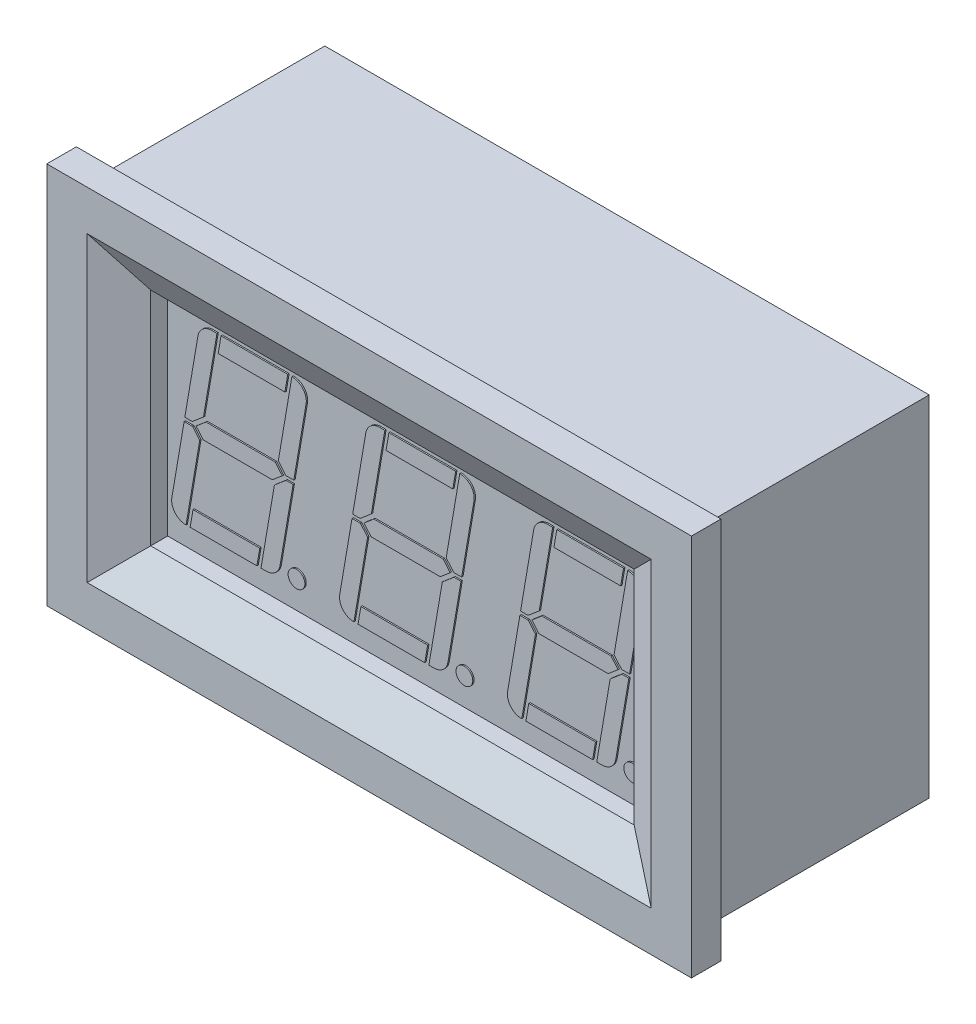
SolidWorks part; units mm, degrees
material "ABS"
ref_plane "Спереди" through (0, 0, 0) normal (0, 0, 1) x (1, 0, 0)
ref_plane "Сверху" through (0, 0, 0) normal (0, 1, 0) x (1, 0, 0)
ref_plane "Справа" through (0, 0, 0) normal (1, 0, 0) x (0, 0, -1)
sketch "Эскиз1" plane through (0, 0, 0) normal (0, 0, 1) x (1, 0, 0)
  line L1 (22.5, -13) -> (-22.5, -13)
  line L2 (22.5, -13) -> (22.5, 13)
  line L3 (22.5, 13) -> (-22.5, 13)
  line L4 (-22.5, -13) -> (-22.5, 13)
  line L5 (22.5, -13) -> (-22.5, 13) construction
  line L6 (22.5, 13) -> (-22.5, -13) construction
  point P0 (0, 0)
  dimension "D1" = 26
  dimension "D2" = 45
extrude "Бобышка-Вытянуть1" add sketch "Эскиз1" along normal blind 17
sketch "Эскиз2" plane through (0, 0, 17) normal (0, 0, 1) x (1, 0, 0)
  line L1 (24, -14.25) -> (-24, -14.25)
  line L2 (24, -14.25) -> (24, 14.25)
  line L3 (24, 14.25) -> (-24, 14.25)
  line L4 (-24, -14.25) -> (-24, 14.25)
  line L5 (24, -14.25) -> (-24, 14.25) construction
  line L6 (24, 14.25) -> (-24, -14.25) construction
  point P0 (0, 0)
  dimension "D1" = 28.5
  dimension "D2" = 48
extrude "Бобышка-Вытянуть2" add sketch "Эскиз2" along normal blind 2.2
sketch "Эскиз3" plane through (0, 0, 19.2) normal (0, 0, 1) x (1, 0, 0)
  line L1 (18, -8.25) -> (-18, -8.25)
  line L2 (18, -8.25) -> (18, 8.25)
  line L3 (18, 8.25) -> (-18, 8.25)
  line L4 (-18, -8.25) -> (-18, 8.25)
  line L5 (18, -8.25) -> (-18, 8.25) construction
  line L6 (18, 8.25) -> (-18, -8.25) construction
  point P0 (0, 0)
  dimension "D1" = 36
  dimension "D2" = 16.5
extrude "Вырез-Вытянуть1" cut sketch "Эскиз3" against normal blind 3
chamfer "Фаска1" distance 3 angle 30 4 edges at (18, 0, 19.2) (0, 8.25, 19.2) (-18, 0, 19.2) (0, -8.25, 19.2)
sketch "Эскиз4" plane through (0, 0, 16.2) normal (0, 0, 1) x (1, 0, 0)
  line L0 (-17.8, -6.75) -> (-16.532, -6.75)
  line L1 (-17.8, -6.75) -> (-16.6756, -0.15)
  line L2 (-9.6847, -6.75) -> (-8.5603, -0.15)
  line L3 (-15.5, 6.75) -> (-14.232, 6.75)
  line L4 (-18, -8.25) -> (18, -8.25) construction
  line L5 (18, 8.25) -> (-18, 8.25) construction
  line L6 (-18, 8.25) -> (-18, -8.25) construction
  line L7 (-8.5347, 0) -> (-16.65, 0) construction
  line L8 (-8.5092, 0.15) -> (-9.099, 0.15)
  line L9 (-9.099, 0.15) -> (-9.6633, 0.8185)
  line L10 (-9.6633, 0.8185) -> (-8.6527, 6.75)
  line L11 (-8.5603, -0.15) -> (-9.0776, -0.15)
  line L12 (-9.0776, -0.15) -> (-9.9544, -0.89)
  line L13 (-9.9544, -0.89) -> (-10.9527, -6.75)
  line L14 (-16.6244, 0.15) -> (-16.0714, 0.15)
  line L15 (-16.0714, 0.15) -> (-15.2364, 0.8548)
  line L16 (-15.2364, 0.8548) -> (-14.232, 6.75)
  line L17 (-16.6756, -0.15) -> (-16.05, -0.15)
  line L18 (-16.05, -0.15) -> (-15.5154, -0.7833)
  line L19 (-15.5154, -0.7833) -> (-16.532, -6.75)
  line L20 (-15.784, 0) -> (-15.0435, 0.625)
  line L21 (-15.0435, 0.625) -> (-9.8925, 0.625)
  line L22 (-9.8925, 0.625) -> (-9.365, 0)
  line L23 (-9.365, 0) -> (-10.1055, -0.625)
  line L24 (-10.1055, -0.625) -> (-15.2565, -0.625)
  line L25 (-15.2565, -0.625) -> (-15.784, 0)
  line L26 (-9.8925, 0.625) -> (-10.1055, -0.625) construction
  line L27 (-15.0435, 0.625) -> (-15.2565, -0.625) construction
  line L28 (-9.6633, 0.8185) -> (-9.8925, 0.625) construction
  line L29 (-15.2364, 0.8548) -> (-15.0435, 0.625) construction
  line L30 (-13.9277, 6.75) -> (-14.1406, 5.5)
  line L31 (-14.1406, 5.5) -> (-9.17, 5.5)
  line L32 (-9.17, 5.5) -> (-8.9571, 6.75)
  line L33 (-16.2277, -6.75) -> (-16.0147, -5.5)
  line L34 (-16.0147, -5.5) -> (-11.0441, -5.5)
  line L35 (-11.0441, -5.5) -> (-11.2571, -6.75)
  line L36 (-10.9527, -6.75) -> (-9.6847, -6.75)
  line L37 (-16.2277, -6.75) -> (-11.2571, -6.75)
  line L38 (-8.5092, 0.15) -> (-7.3847, 6.75)
  line L39 (-8.6527, 6.75) -> (-7.3847, 6.75)
  line L40 (-13.9277, 6.75) -> (-8.9571, 6.75)
  line L41 (-16.6244, 0.15) -> (-15.5, 6.75)
  line L42 (-9.6847, -6.75) -> (-6.2012, -6.75) construction
  circle A0 centre (-8.3102, -6.125) radius 0.625
  dimension "D22" = 1.25
  dimension "D1" = 1.5
  dimension "D2" = 1.5
  dimension "D3" = 0.2
  dimension "D4" = 2.5
  dimension "D5" = 8
  dimension "D6" = 0.15
  dimension "D7" = 1.25
  dimension "D8" = 0.3
  dimension "D9" = 1.25
  dimension "D10" = 1.25
  dimension "D11" = 0.625
  dimension "D12" = 0.3
  dimension "D13" = 0.3
  dimension "D14" = 0.3
  dimension "D15" = 0.3
  dimension "D16" = 40.167
  dimension "D17" = 50
  dimension "D18" = 0.3
  dimension "D19" = 0.3
  dimension "D20" = 1.25
  dimension "D21" = 6.75
  dimension "D23" = 1.25
extrude "Бобышка-Вытянуть3" add sketch "Эскиз4" along normal blind 0.1
fillet "Скругление1" radius 1.05 4 edges at (-9.6847, -6.75, 16.25) (-17.8, -6.75, 16.25) (-15.5, 6.75, 16.25) (-7.3847, 6.75, 16.25)
pattern_linear "Линейный массив1" count 3 spacing 12.5 along (1, 0, 0) of "Бобышка-Вытянуть3", "Скругление1"
